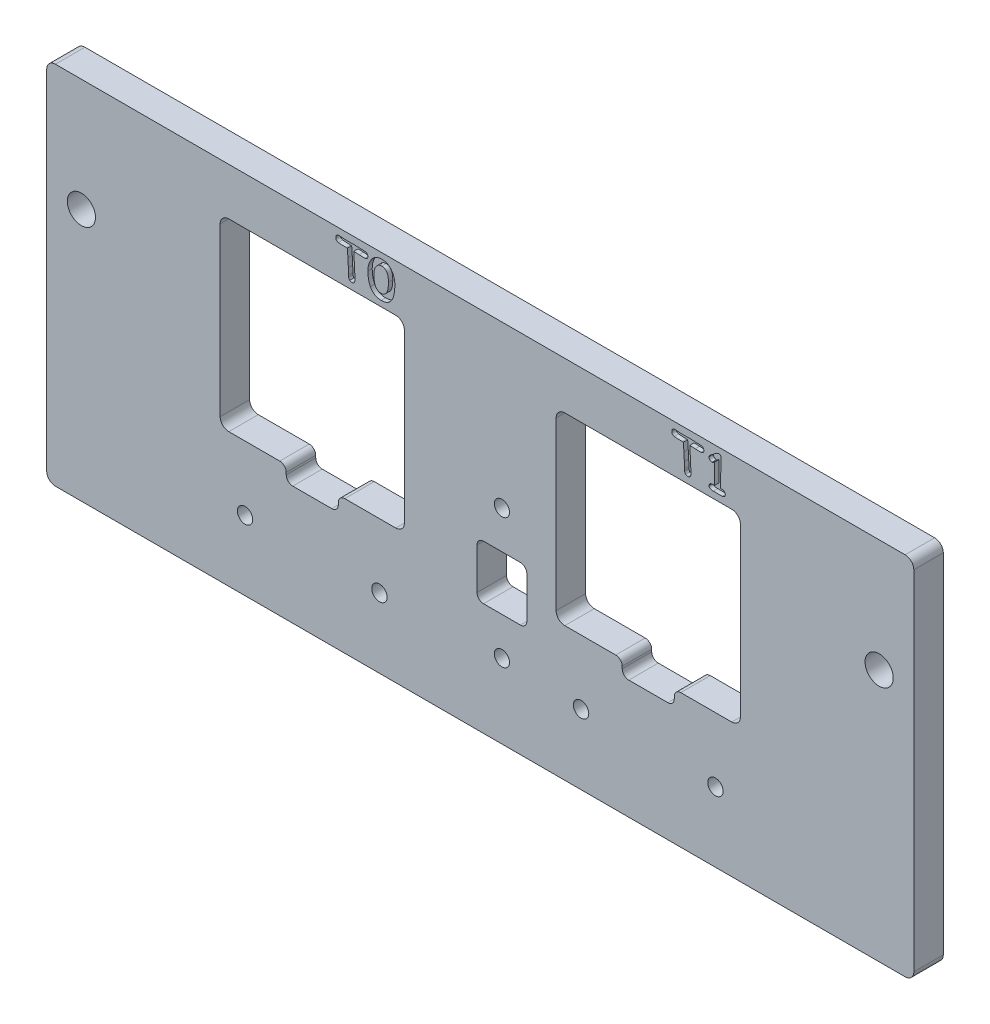
SolidWorks part; units mm, degrees
ref_plane "Front Plane" through (0, 0, 0) normal (0, 0, 1) x (1, 0, 0)
ref_plane "Top Plane" through (0, 0, 0) normal (0, 1, 0) x (1, 0, 0)
ref_plane "Right Plane" through (0, 0, 0) normal (1, 0, 0) x (0, 0, -1)
sketch "Sketch1" plane through (0, 0, 0) normal (0, 0, 1) x (1, 0, 0)
  line L1 (100, -42.15) -> (-100, -42.15)
  line L2 (100, -42.15) -> (100, 42.15)
  line L3 (100, 42.15) -> (-100, 42.15)
  line L4 (-100, -42.15) -> (-100, 42.15)
  line L5 (100, -42.15) -> (-100, 42.15) construction
  line L6 (100, 42.15) -> (-100, -42.15) construction
  point P0 (0, 0)
  dimension "D1" = 200
  dimension "D2" = 84.3
extrude "Boss-Extrude1" add sketch "Sketch1" along normal blind 6.8
sketch "Sketch2" plane through (0, 0, 6.8) normal (0, 0, 1) x (1, 0, 0)
  line L0 (100, 42.15) -> (-100, 42.15) construction
  line L1 (92, 16.15) -> (-92, 16.15) construction
  circle A0 centre (-92, 16.15) radius 3.25
  circle A1 centre (92, 16.15) radius 3.25
  point P10 (0, 16.15)
  dimension "D1" = 6.5
  dimension "D2" = 92
  dimension "D3" = 26
extrude "Cut-Extrude1" cut sketch "Sketch2" against normal blind 6.8
fillet "Fillet1" radius 2 4 edges at (100, 42.15, 3.4) (100, -42.15, 3.4) (-100, -42.15, 3.4) (-100, 42.15, 3.4)
sketch "Sketch3" plane through (0, 0, 6.8) normal (0, 0, 1) x (1, 0, 0)
  line L0 (100, -40.15) -> (100, 40.15) construction
  line L1 (60, -11.25) -> (17.5, -11.25)
  line L2 (60, -11.25) -> (60, 31.25)
  line L3 (60, 31.25) -> (17.5, 31.25)
  line L4 (17.5, -11.25) -> (17.5, 31.25)
  line L5 (60, -11.25) -> (17.5, 31.25) construction
  line L6 (60, 31.25) -> (17.5, -11.25) construction
  line L7 (54.25, -26.082) -> (23.25, -26.082) construction
  circle A0 centre (23.25, -26.082) radius 1.775
  circle A1 centre (54.25, -26.082) radius 1.775
  point P0 (38.75, 10)
  point P16 (38.75, -26.082)
  dimension "D6" = 3.55
  dimension "D1" = 42.5
  dimension "D2" = 40
  dimension "D3" = 10
  dimension "D4" = 14.832
  dimension "D5" = 31
extrude "Cut-Extrude2" cut sketch "Sketch3" against normal through all
fillet "Fillet2" radius 2 4 edges at (60, 31.25, 3.4) (17.5, 31.25, 3.4) (17.5, -11.25, 3.4) (60, -11.25, 3.4)
mirror "Mirror1" [suppressed] about plane through (0, 0, 0) normal (1, 0, 0)
sketch "Sketch4" plane through (0, 0, 6.8) normal (0, 0, 1) x (1, 0, 0)
  line L1 (44.75, -14.75) -> (32.75, -14.75)
  line L2 (44.75, -14.75) -> (44.75, -7.75)
  line L3 (44.75, -7.75) -> (32.75, -7.75)
  line L4 (32.75, -14.75) -> (32.75, -7.75)
  line L5 (44.75, -14.75) -> (32.75, -7.75) construction
  line L6 (44.75, -7.75) -> (32.75, -14.75) construction
  line L7 (19.5, -11.25) -> (58, -11.25) construction
  point P0 (38.75, -11.25)
  dimension "D1" = 3.5
  dimension "D2" = 12
extrude "Cut-Extrude3" cut sketch "Sketch4" against normal through all
fillet "Fillet3" radius 1.5 4 edges at (44.75, -14.75, 3.4) (32.75, -14.75, 3.4) (32.75, -11.25, 3.4) (44.75, -11.25, 3.4)
sketch "Sketch5" plane through (0, 0, 6.8) normal (0, 0, 1) x (1, 0, 0)
  line L0 (0, 5) -> (0, -25) construction
  line L1 (5.75, -16.25) -> (-5.75, -16.25)
  line L2 (5.75, -16.25) -> (5.75, -3.75)
  line L3 (5.75, -3.75) -> (-5.75, -3.75)
  line L4 (-5.75, -16.25) -> (-5.75, -3.75)
  line L5 (5.75, -16.25) -> (-5.75, -3.75) construction
  line L6 (5.75, -3.75) -> (-5.75, -16.25) construction
  circle A0 centre (0, -25) radius 1.75
  circle A1 centre (0, 5) radius 1.75
  point P0 (0, -10)
  point P10 (0, -10)
  dimension "D4" = 3.5
  dimension "D1" = 12.5
  dimension "D2" = 11.5
  dimension "D3" = 30
  dimension "D5" = 10
extrude "Cut-Extrude4" cut sketch "Sketch5" against normal through all
fillet "Fillet4" radius 1.5 4 edges at (-5.75, -3.75, 3.4) (5.75, -3.75, 3.4) (5.75, -16.25, 3.4) (-5.75, -16.25, 3.4)
mirror "Mirror2" about plane through (0, 0, 0) normal (1, 0, 0) of "Fillet2", "Cut-Extrude2", "Cut-Extrude3", "Fillet3"
sketch "Sketch6" plane through (0, 0, 6.8) normal (0, 0, 1) x (1, 0, 0)
  line L0 (-58, 32.75) -> (-19.5, 32.75) construction
  line L1 (-58, 31.25) -> (-19.5, 31.25) construction
  line L2 (19.5, 32.75) -> (58, 32.75) construction
  text T0 "T0" font "Comic Sans MS" height 8
  text T1 "T1" font "Comic Sans MS" height 8
  point P7 (0, 0)
  dimension "D1" = 1.5
extrude "Cut-Extrude5" cut sketch "Sketch6" against normal blind 1
sketch "Sketch7" plane through (0, 0, 6.8) normal (0, 0, 1) x (1, 0, 0)
  line L1 (-10.1813, 10.0691) -> (11.0994, 10.0691)
  line L2 (-10.1813, 10.0691) -> (-10.1813, -31.1835)
  line L3 (-10.1813, -31.1835) -> (11.0994, -31.1835)
  line L4 (11.0994, 10.0691) -> (11.0994, -31.1835)
extrude "Boss-Extrude2" add sketch "Sketch7" against normal up to vertex (6.8 mm away)
sketch "Sketch8" plane through (0, 0, 6.8) normal (0, 0, 1) x (1, 0, 0)
  line L0 (5, 5) -> (5, -10) construction
  line L1 (10.75, -16.25) -> (-0.75, -16.25)
  line L2 (10.75, -16.25) -> (10.75, -3.75)
  line L3 (10.75, -3.75) -> (-0.75, -3.75)
  line L4 (-0.75, -16.25) -> (-0.75, -3.75)
  line L5 (10.75, -16.25) -> (-0.75, -3.75) construction
  line L6 (10.75, -3.75) -> (-0.75, -16.25) construction
  line L7 (5, -10) -> (5, -25) construction
  circle A0 centre (5, -25) radius 1.75
  circle A1 centre (5, 5) radius 1.75
  point P0 (5, -10)
  dimension "D1" = 3.5
  dimension "D2" = 10
  dimension "D3" = 30
  dimension "D4" = 12.5
  dimension "D5" = 11.5
  dimension "D6" = 5
extrude "Cut-Extrude6" cut sketch "Sketch8" against normal through all
fillet "Fillet5" radius 1.5 4 edges at (10.75, -16.25, 3.4) (-0.75, -16.25, 3.4) (-0.75, -3.75, 3.4) (10.75, -3.75, 3.4)
